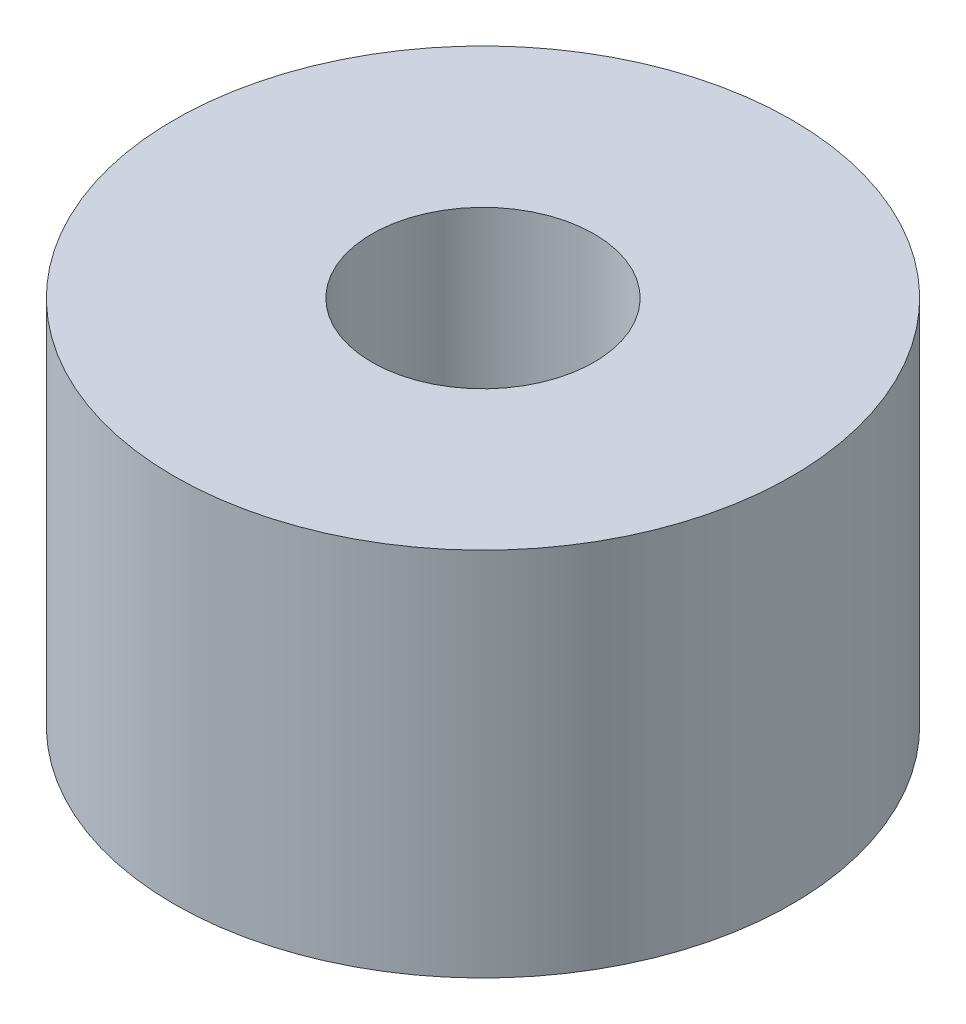
SolidWorks part; units mm, degrees
material "ABS"
ref_plane "前视基准面" through (0, 0, 0) normal (0, 0, 1) x (1, 0, 0)
ref_plane "上视基准面" through (0, 0, 0) normal (0, 1, 0) x (1, 0, 0)
ref_plane "右视基准面" through (0, 0, 0) normal (1, 0, 0) x (0, 0, -1)
other "Configuration Table"
sketch "草图1" plane through (0, 0, 0) normal (0, 1, 0) x (1, 0, 0)
  circle A0 centre (0, 0) radius 1.8
  circle A1 centre (0, 0) radius 5
  dimension "D1" = 3.6
  dimension "D2" = 10
extrude "凸台-拉伸1" add sketch "草图1" along normal blind 6
